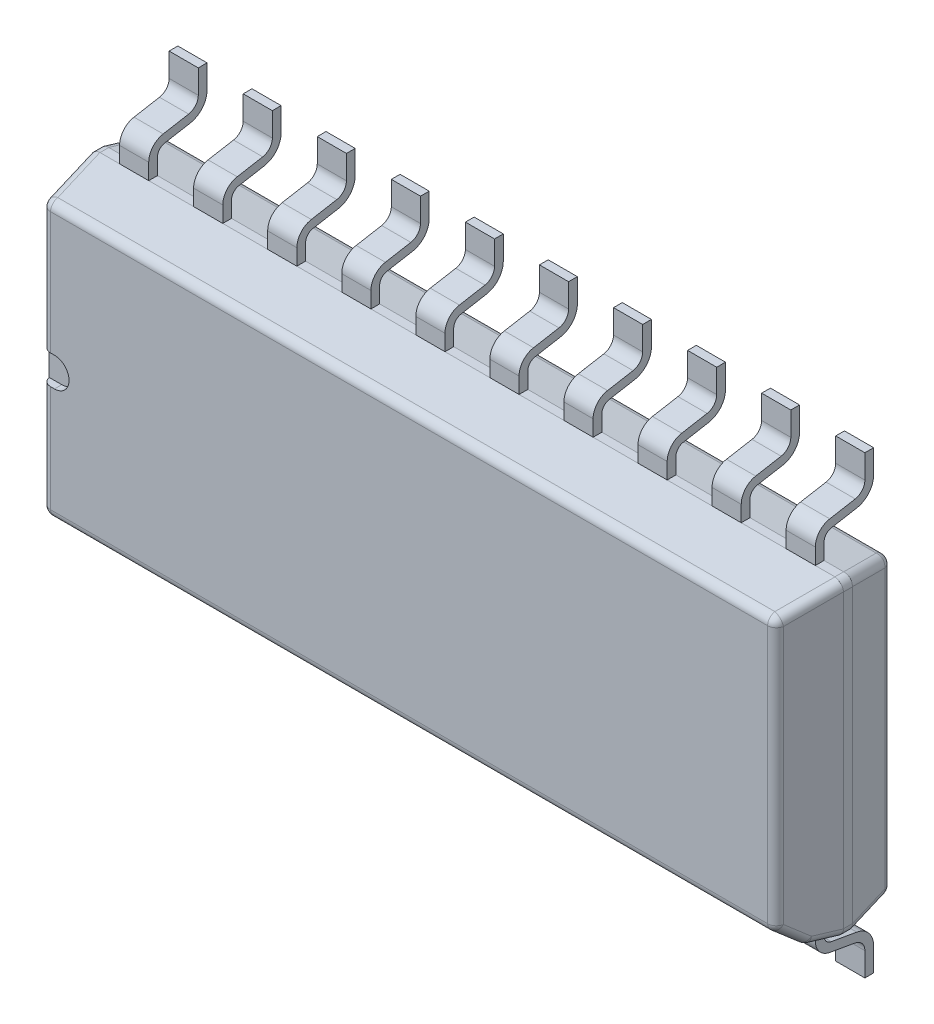
SolidWorks part; units mm, degrees
ref_plane "Front Plane" through (0, 0, 0) normal (0, 0, 1) x (1, 0, 0)
ref_plane "Top Plane" through (0, 0, 0) normal (0, 1, 0) x (1, 0, 0)
ref_plane "Right Plane" through (0, 0, 0) normal (1, 0, 0) x (0, 0, -1)
sketch "Sketch1" plane through (0, 0, 0) normal (0, 0, 1) x (1, 0, 0)
  line L0 (-4.695, -3.9) -> (-4.195, -3.9)
  line L1 (-5.965, -3.9) -> (-5.465, -3.9)
  line L2 (-5.965, -3.9) -> (-5.965, -2.65)
  line L3 (-5.965, -2.65) -> (-5.465, -2.65)
  line L4 (-5.465, -3.9) -> (-5.465, -2.65)
  line L5 (-5.965, -3.9) -> (-5.465, -2.65) construction
  line L6 (-5.965, -2.65) -> (-5.465, -3.9) construction
  line L7 (-4.695, -3.9) -> (-4.695, -2.65)
  line L8 (-4.695, -2.65) -> (-4.195, -2.65)
  line L9 (-4.195, -3.9) -> (-4.195, -2.65)
  line L10 (-4.695, -3.9) -> (-4.195, -2.65) construction
  line L11 (-4.695, -2.65) -> (-4.195, -3.9) construction
  line L12 (-3.425, -3.9) -> (-2.925, -3.9)
  line L13 (-3.425, -3.9) -> (-3.425, -2.65)
  line L14 (-3.425, -2.65) -> (-2.925, -2.65)
  line L15 (-2.925, -3.9) -> (-2.925, -2.65)
  line L16 (-3.425, -3.9) -> (-2.925, -2.65) construction
  line L17 (-3.425, -2.65) -> (-2.925, -3.9) construction
  line L18 (-2.155, -3.9) -> (-1.655, -3.9)
  line L19 (-2.155, -3.9) -> (-2.155, -2.65)
  line L20 (-2.155, -2.65) -> (-1.655, -2.65)
  line L21 (-1.655, -3.9) -> (-1.655, -2.65)
  line L22 (-2.155, -3.9) -> (-1.655, -2.65) construction
  line L23 (-2.155, -2.65) -> (-1.655, -3.9) construction
  line L24 (-0.885, -3.9) -> (-0.385, -3.9)
  line L25 (-0.885, -3.9) -> (-0.885, -2.65)
  line L26 (-0.885, -2.65) -> (-0.385, -2.65)
  line L27 (-0.385, -3.9) -> (-0.385, -2.65)
  line L28 (-0.885, -3.9) -> (-0.385, -2.65) construction
  line L29 (-0.885, -2.65) -> (-0.385, -3.9) construction
  line L30 (0.385, -3.9) -> (0.885, -3.9)
  line L31 (0.385, -3.9) -> (0.385, -2.65)
  line L32 (0.385, -2.65) -> (0.885, -2.65)
  line L33 (0.885, -3.9) -> (0.885, -2.65)
  line L34 (0.385, -3.9) -> (0.885, -2.65) construction
  line L35 (0.385, -2.65) -> (0.885, -3.9) construction
  line L36 (1.655, -3.9) -> (2.155, -3.9)
  line L37 (1.655, -3.9) -> (1.655, -2.65)
  line L38 (1.655, -2.65) -> (2.155, -2.65)
  line L39 (2.155, -3.9) -> (2.155, -2.65)
  line L40 (1.655, -3.9) -> (2.155, -2.65) construction
  line L41 (1.655, -2.65) -> (2.155, -3.9) construction
  line L42 (2.925, -3.9) -> (3.425, -3.9)
  line L43 (2.925, -3.9) -> (2.925, -2.65)
  line L44 (2.925, -2.65) -> (3.425, -2.65)
  line L45 (3.425, -3.9) -> (3.425, -2.65)
  line L46 (2.925, -3.9) -> (3.425, -2.65) construction
  line L47 (2.925, -2.65) -> (3.425, -3.9) construction
  line L48 (4.195, -3.9) -> (4.695, -3.9)
  line L49 (4.195, -3.9) -> (4.195, -2.65)
  line L50 (4.195, -2.65) -> (4.695, -2.65)
  line L51 (4.695, -3.9) -> (4.695, -2.65)
  line L52 (4.195, -3.9) -> (4.695, -2.65) construction
  line L53 (4.195, -2.65) -> (4.695, -3.9) construction
  line L54 (5.465, -3.9) -> (5.965, -3.9)
  line L55 (5.465, -3.9) -> (5.465, -2.65)
  line L56 (5.465, -2.65) -> (5.965, -2.65)
  line L57 (5.965, -3.9) -> (5.965, -2.65)
  line L58 (5.465, -3.9) -> (5.965, -2.65) construction
  line L59 (5.465, -2.65) -> (5.965, -3.9) construction
  line L60 (-7.5525, 0) -> (7.8266, 0) construction
  line L61 (5.465, 3.9) -> (5.965, 2.65) construction
  line L62 (4.195, 2.65) -> (4.695, 3.9) construction
  line L63 (4.195, 3.9) -> (4.695, 2.65) construction
  line L64 (2.925, 2.65) -> (3.425, 3.9) construction
  line L65 (2.925, 3.9) -> (3.425, 2.65) construction
  line L66 (1.655, 2.65) -> (2.155, 3.9) construction
  line L67 (1.655, 3.9) -> (2.155, 2.65) construction
  line L68 (0.385, 2.65) -> (0.885, 3.9) construction
  line L69 (0.385, 3.9) -> (0.885, 2.65) construction
  line L70 (-0.885, 2.65) -> (-0.385, 3.9) construction
  line L71 (-0.885, 3.9) -> (-0.385, 2.65) construction
  line L72 (-2.155, 2.65) -> (-1.655, 3.9) construction
  line L73 (-2.155, 3.9) -> (-1.655, 2.65) construction
  line L74 (-3.425, 2.65) -> (-2.925, 3.9) construction
  line L75 (-3.425, 3.9) -> (-2.925, 2.65) construction
  line L76 (-4.695, 2.65) -> (-4.195, 3.9) construction
  line L77 (-4.695, 3.9) -> (-4.195, 2.65) construction
  line L78 (-5.965, 2.65) -> (-5.465, 3.9) construction
  line L79 (-5.965, 3.9) -> (-5.465, 2.65) construction
  line L80 (5.965, 3.9) -> (5.965, 2.65)
  line L81 (5.465, 2.65) -> (5.965, 2.65)
  line L82 (5.465, 3.9) -> (5.465, 2.65)
  line L83 (5.465, 3.9) -> (5.965, 3.9)
  line L84 (4.695, 3.9) -> (4.695, 2.65)
  line L85 (4.195, 2.65) -> (4.695, 2.65)
  line L86 (4.195, 3.9) -> (4.195, 2.65)
  line L87 (4.195, 3.9) -> (4.695, 3.9)
  line L88 (3.425, 3.9) -> (3.425, 2.65)
  line L89 (2.925, 2.65) -> (3.425, 2.65)
  line L90 (2.925, 3.9) -> (2.925, 2.65)
  line L91 (2.925, 3.9) -> (3.425, 3.9)
  line L92 (2.155, 3.9) -> (2.155, 2.65)
  line L93 (1.655, 2.65) -> (2.155, 2.65)
  line L94 (1.655, 3.9) -> (1.655, 2.65)
  line L95 (1.655, 3.9) -> (2.155, 3.9)
  line L96 (0.885, 3.9) -> (0.885, 2.65)
  line L97 (0.385, 2.65) -> (0.885, 2.65)
  line L98 (0.385, 3.9) -> (0.385, 2.65)
  line L99 (0.385, 3.9) -> (0.885, 3.9)
  line L100 (-0.385, 3.9) -> (-0.385, 2.65)
  line L101 (-0.885, 2.65) -> (-0.385, 2.65)
  line L102 (-0.885, 3.9) -> (-0.885, 2.65)
  line L103 (-0.885, 3.9) -> (-0.385, 3.9)
  line L104 (-1.655, 3.9) -> (-1.655, 2.65)
  line L105 (-2.155, 2.65) -> (-1.655, 2.65)
  line L106 (-2.155, 3.9) -> (-2.155, 2.65)
  line L107 (-2.155, 3.9) -> (-1.655, 3.9)
  line L108 (-2.925, 3.9) -> (-2.925, 2.65)
  line L109 (-3.425, 2.65) -> (-2.925, 2.65)
  line L110 (-3.425, 3.9) -> (-3.425, 2.65)
  line L111 (-3.425, 3.9) -> (-2.925, 3.9)
  line L112 (-4.195, 3.9) -> (-4.195, 2.65)
  line L113 (-4.695, 2.65) -> (-4.195, 2.65)
  line L114 (-4.695, 3.9) -> (-4.695, 2.65)
  line L115 (-5.465, 3.9) -> (-5.465, 2.65)
  line L116 (-5.965, 2.65) -> (-5.465, 2.65)
  line L117 (-5.965, 3.9) -> (-5.965, 2.65)
  line L118 (-5.965, 3.9) -> (-5.465, 3.9)
  line L119 (-4.695, 3.9) -> (-4.195, 3.9)
  point P0 (-5.715, -3.275)
  point P1 (-5.715, -3.275)
  point P7 (-4.445, -3.275)
  point P8 (-4.445, -3.275)
  point P13 (-3.175, -3.275)
  point P14 (-3.175, -3.275)
  point P19 (-1.905, -3.275)
  point P20 (-1.905, -3.275)
  point P25 (-0.635, -3.275)
  point P26 (-0.635, -3.275)
  point P31 (0.635, -3.275)
  point P32 (0.635, -3.275)
  point P37 (1.905, -3.275)
  point P38 (1.905, -3.275)
  point P43 (3.175, -3.275)
  point P44 (3.175, -3.275)
  point P49 (4.445, -3.275)
  point P50 (4.445, -3.275)
  point P55 (5.715, -3.275)
  point P56 (5.715, -3.275)
  point P103 (5.715, 3.275)
  point P104 (4.445, 3.275)
  point P105 (3.175, 3.275)
  point P106 (1.905, 3.275)
  point P107 (0.635, 3.275)
  point P108 (-0.635, 3.275)
  point P109 (-1.905, 3.275)
  point P110 (-3.175, 3.275)
  point P111 (-4.445, 3.275)
  point P112 (-5.715, 3.275)
  dimension "D1" = 10
extrude "Boss-Extrude1" add sketch "Sketch1" along normal blind 1
sketch "Sketch2" plane through (-5.965, 0, 0) normal (-1, 0, 0) x (0, 0, 1)
  line L0 (0, 3.9) -> (0, 2.65) construction
  line L1 (1, 3.9) -> (0, 3.9) construction
  line L2 (1, 2.65) -> (0, 2.65) construction
  line L3 (0.85, 2.65) -> (0.85, 3.9) construction
  line L4 (0.15, 3.9) -> (0.15, 2.65) construction
  line L5 (0, 3.4937) -> (0, 2.65)
  line L6 (0.2892, 3.149) -> (0.726, 3.072)
  line L7 (0.85, 2.9243) -> (0.85, 2.65)
  line L8 (0, 2.65) -> (0.85, 2.65)
  line L9 (0.15, 3.9) -> (0.15, 3.4937)
  line L10 (0.3153, 3.2967) -> (0.7521, 3.2197)
  line L11 (1, 3.9) -> (1, 2.65) construction
  line L12 (0.15, 3.9) -> (1, 3.9)
  line L13 (1, 2.9243) -> (1, 2.65) construction
  line L14 (0, 3.9) -> (0, 3.4937) construction
  line L15 (1, 3.9) -> (1, 2.9243)
  line L16 (-1.272, 0) -> (2.529, 0) construction
  line L17 (0.15, -3.9) -> (0.15, -2.65) construction
  line L18 (0.85, -2.65) -> (0.85, -3.9) construction
  line L19 (1, -3.9) -> (1, -2.9243)
  line L20 (0.15, -3.9) -> (1, -3.9)
  line L21 (0.3153, -3.2967) -> (0.7521, -3.2197)
  line L22 (0.15, -3.9) -> (0.15, -3.4937)
  line L23 (0, -2.65) -> (0.85, -2.65)
  line L24 (0.85, -2.9243) -> (0.85, -2.65)
  line L25 (0.2892, -3.149) -> (0.726, -3.072)
  line L26 (0, -3.4937) -> (0, -2.65)
  arc A0 (0.3153, 3.2967) -> (0.15, 3.4937) centre (0.35, 3.4937) cw
  arc A1 (1, 2.9243) -> (0.7521, 3.2197) centre (0.7, 2.9243) ccw
  arc A2 (0.2892, 3.149) -> (0, 3.4937) centre (0.35, 3.4937) cw
  arc A3 (0.85, 2.9243) -> (0.726, 3.072) centre (0.7, 2.9243) ccw
  arc A4 (0.85, -2.9243) -> (0.726, -3.072) centre (0.7, -2.9243) cw
  arc A5 (0.2892, -3.149) -> (0, -3.4937) centre (0.35, -3.4937) ccw
  arc A6 (1, -2.9243) -> (0.7521, -3.2197) centre (0.7, -2.9243) cw
  arc A7 (0.3153, -3.2967) -> (0.15, -3.4937) centre (0.35, -3.4937) ccw
  point P0 (0, 3.2)
  point P1 (0.15, 3.9)
  point P5 (0.85, 2.65)
  point P20 (1, 3.176)
  point P45 (1, -3.176)
  point P47 (0, -3.2)
extrude "Cut-Extrude1" cut sketch "Sketch2" against normal through all
ref_plane "Plane1" through (0, 0, 0.05) normal (0, 0, 1) x (1, 0, 0)
sketch "Sketch3" plane through (0, 0, 0.05) normal (0, 0, 1) x (1, 0, 0)
  line L1 (-6.45, -2.65) -> (6.45, -2.65)
  line L2 (-6.45, -2.65) -> (-6.45, 2.65)
  line L3 (-6.45, 2.65) -> (6.45, 2.65)
  line L4 (6.45, -2.65) -> (6.45, 2.65)
  line L5 (-6.45, -2.65) -> (6.45, 2.65) construction
  line L6 (-6.45, 2.65) -> (6.45, -2.65) construction
  point P0 (0, 0)
extrude "Boss-Extrude2" add sketch "Sketch3" along normal blind 1.95 separate body
chamfer "Chamfer1" distance 1 angle 10 4 edges at (0, 2.65, 2) (0, -2.65, 2) (6.45, 0, 2) (-6.45, 0, 2)
chamfer "Chamfer2" distance 0.8 angle 10 4 edges at (-6.45, 0, 0.05) (0, -2.65, 0.05) (6.45, 0, 0.05) (0, 2.65, 0.05)
chamfer "Chamfer3" distance 0.5 angle 30 1 edges at (0, -2.4737, 2)
fillet "Fillet1" radius 0.15 23 edges at (-6.2737, 0.1632, 2) (0, 2.4737, 2) (6.2737, 0.1632, 2) (-6.4052, -2.6052, 1.2538) (-6.3618, 2.5618, 1.5) (6.3618, 2.5618, 1.5) (6.45, 2.65, 0.925) (6.45, -2.65, 0.925) (6.3795, 2.5795, 0.45) (6.3795, -2.5795, 0.45) (6.4052, -2.6052, 1.2538) (6.3089, 0, 0.05) (0, 2.5089, 0.05) (-6.3089, 0, 0.05) (0, -2.5089, 0.05) (-6.45, 2.65, 0.925) (-6.3795, 2.5795, 0.45) (-6.3795, -2.5795, 0.45) (-6.45, -2.65, 0.925) (6.3171, -2.3539, 1.7538) (0, -2.5605, 1.5076) (-6.3171, -2.3539, 1.7538) (0, -2.1473, 2)
sketch "Sketch4" plane through (0, 0, 2) normal (0, 0, 1) x (1, 0, 0)
  line L0 (0, 0) -> (-6.6484, 0) construction
  line L3 (-6.45, -2.5) -> (-6.45, 2.5) construction
  line L4 (-6.3308, 2.3831) -> (-6.3308, -2.3831) construction
  line L5 (-6.45, 0.25) -> (-6.0808, 0.25)
  line L6 (-6.0808, -0.25) -> (-6.45, -0.25)
  line L7 (-6.45, -0.25) -> (-6.45, 0.25)
  circle A0 centre (-6.0808, 0) radius 0.25 construction
  arc A1 (-6.0808, 0.25) -> (-6.0808, -0.25) centre (-6.0808, 0) cw
  point P2 (-6.45, 0.25)
  point P3 (-6.3308, 0)
  point P6 (-6.0808, 0)
  dimension "D2" = 0.25
  dimension "D1" = 0.25
extrude "Cut-Extrude2" cut sketch "Sketch4" against normal blind 0.125
